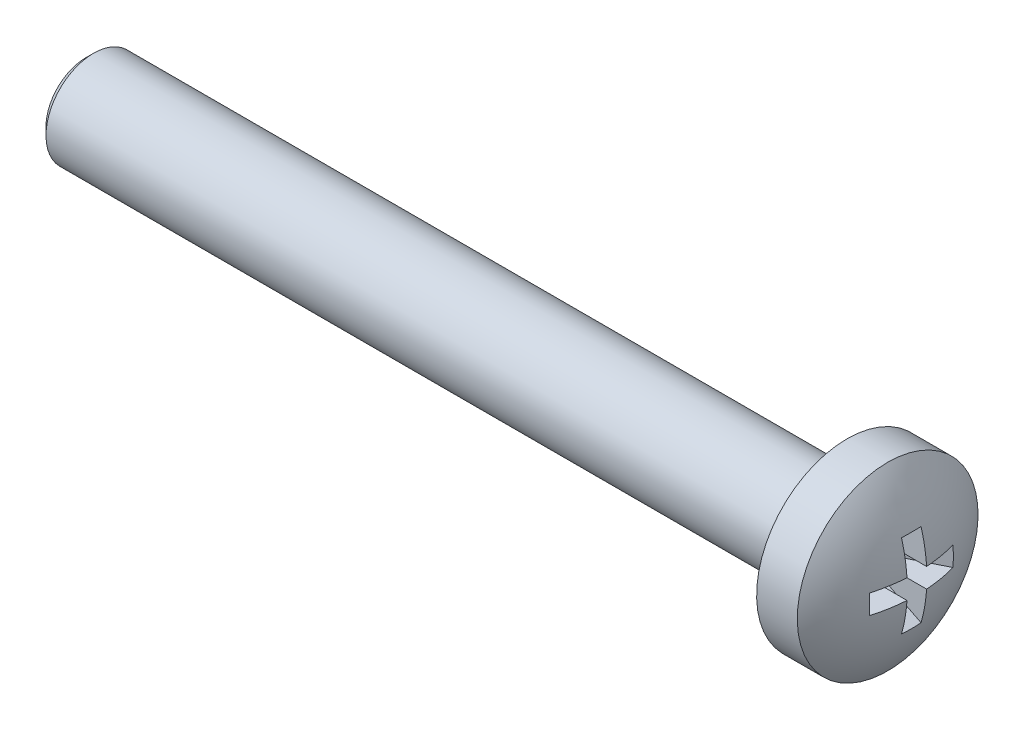
SolidWorks part; units mm, degrees
material "AISI 1020"
ref_plane "Front Plane" through (0, 0, 0) normal (0, 0, 1) x (1, 0, 0)
ref_plane "Top Plane" through (0, 0, 0) normal (0, 1, 0) x (1, 0, 0)
ref_plane "Right Plane" through (0, 0, 0) normal (1, 0, 0) x (0, 0, -1)
sketch "Sketch1" plane through (0, 0, 0) normal (0, 0, 1) x (1, 0, 0)
  line L0 (0, 0) -> (-43.7, 0) construction
  line L1 (-43.7, 0) -> (-43.7, 2.5)
  line L2 (-43.7, 2.5) -> (-3.7, 2.5)
  line L3 (-3.7, 2.5) -> (-3.7, 4.75)
  line L4 (-3.7, 4.75) -> (-1.5628, 4.75)
  line L5 (0, 0) -> (-43.7, 0)
  arc A0 (-1.5628, 4.75) -> (0, 0) centre (-8, 0) cw
  dimension "G_radius" = 8
  dimension "Diam" = 5
  dimension "G_diam" = 9.5
  dimension "G_plotis" = 3.7
  dimension "Ilgis" = 40
revolve "Revolve1" add sketch "Sketch1" angle 360 about L0
cosmetic thread "Cosmetic Thread1" parameters "Sr_ilgis"=40, "Sr_diam"=4.2
sketch "Sketch2" plane through (0, 0, 0) normal (1, 0, 0) x (0, 0, -1)
  line L0 (-2.35, -0.515) -> (2.35, 0.515) construction
  line L1 (-0.515, 2.35) -> (0.515, 2.35)
  line L2 (-0.515, 2.35) -> (-0.515, -2.35)
  line L3 (-0.515, -2.35) -> (0.515, -2.35)
  line L4 (0.515, 2.35) -> (0.515, -2.35)
  line L5 (-2.35, 0.515) -> (2.35, 0.515)
  line L6 (-2.35, 0.515) -> (-2.35, -0.515)
  line L7 (-2.35, -0.515) -> (2.35, -0.515)
  line L8 (2.35, 0.515) -> (2.35, -0.515)
  line L9 (-0.515, -2.35) -> (0.515, 2.35) construction
  dimension "Y_plotis" = 1.03
  dimension "Y_ilgis" = 4.7
extrude "Cut-Extrude1" cut sketch "Sketch2" against normal blind 2.74 contours L6 L7 L2 L5 | L2 L5 L4 L1 | L2 L7 L4 L5 | L7 L2 L3 L4 | L8 L5 L4 L7
chamfer "Chamfer1" distance 0.4 angle 45 1 edges at (-43.7, 2.5, 0)
draft "Draft1" type of draft neutral plane draft angle 26.5 neutral plane "Right Plane" faces to draft 4 face at (-1.5508, 0, -2.35) face at (-1.5508, -2.35, 0) face at (-1.5508, 2.35, 0) face at (-1.5508, 0, 2.35) neutral plane through (0, 0, 0) neutral plane normal (1, 0, 0) parameters "D1"=26.5
